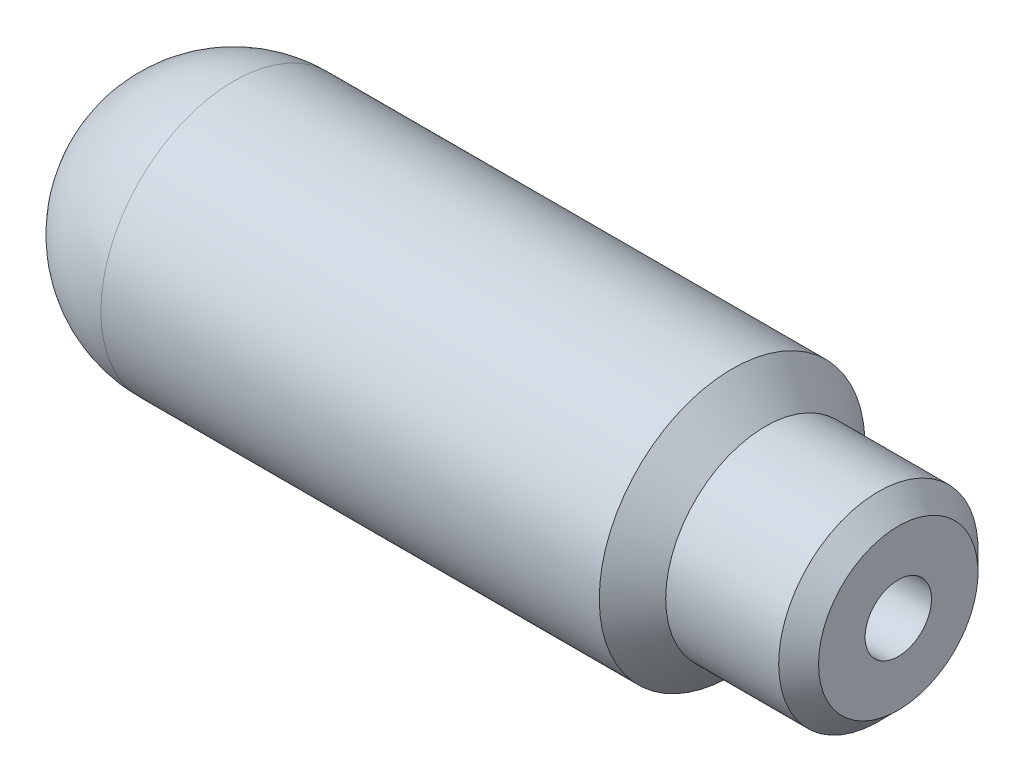
SolidWorks part; units mm, degrees
ref_plane "Front Plane" through (0, 0, 0) normal (0, 0, 1) x (1, 0, 0)
ref_plane "Top Plane" through (0, 0, 0) normal (0, 1, 0) x (1, 0, 0)
ref_plane "Right Plane" through (0, 0, 0) normal (1, 0, 0) x (0, 0, -1)
sketch "Sketch1" plane through (0, 0, 0) normal (0, 0, 1) x (1, 0, 0)
  line L0 (0, 0) -> (95, 0)
  line L1 (55, 0) -> (-55, 0) construction
  line L2 (95, 0) -> (95, 5)
  line L3 (95, 5) -> (120, 5)
  line L4 (120, 5) -> (120, 12)
  line L5 (117, 15) -> (100, 15)
  line L6 (100, 15) -> (95, 20)
  line L7 (95, 20) -> (20, 20)
  line L8 (0, 0) -> (137.797, 0) construction
  line L9 (120, 12) -> (117, 15)
  arc A0 (20, 20) -> (0, 0) centre (20, 0) ccw
  point P8 (120, 15)
  dimension "D1" = 40
  dimension "D2" = 5
  dimension "D3" = 25
  dimension "D4" = 15
  dimension "D5" = 20
  dimension "D6" = 95
  dimension "D7" = 135
  dimension "D8" = 20
revolve "Revolve1" add sketch "Sketch1" angle 360 about L8
